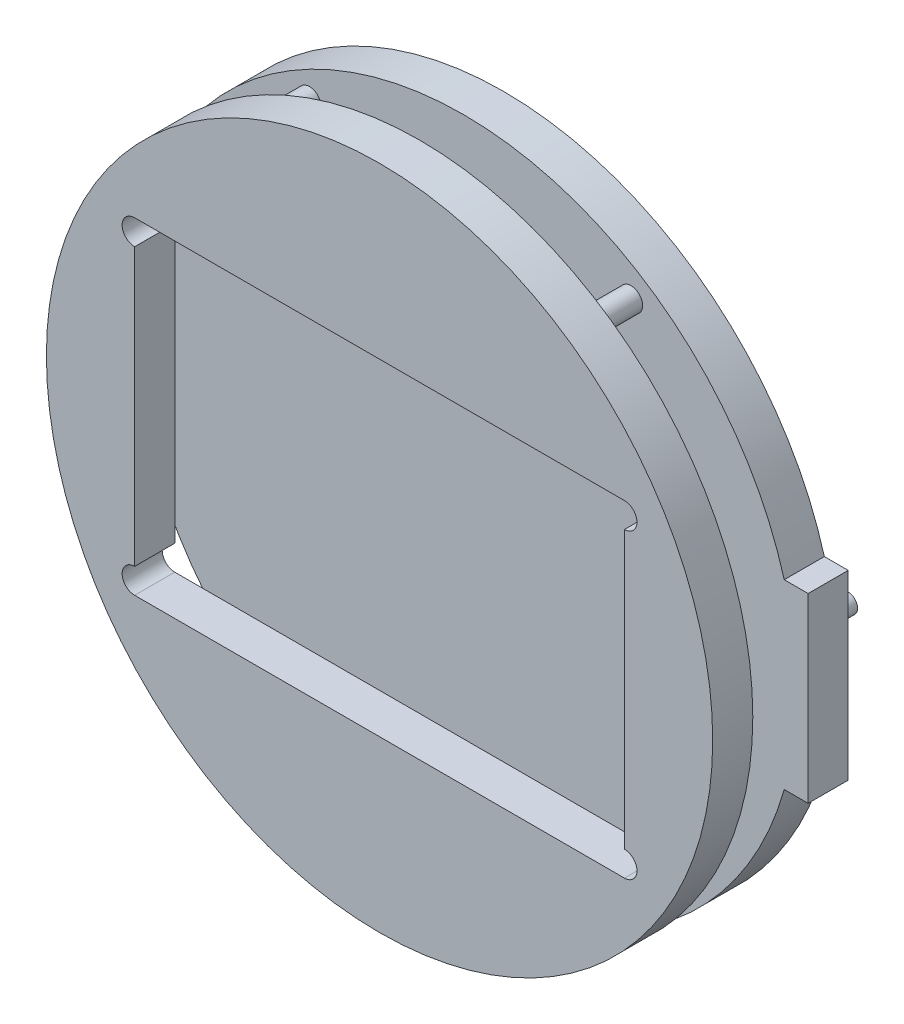
SolidWorks part; units mm, degrees
ref_plane "Front Plane" through (0, 0, 0) normal (0, 0, 1) x (1, 0, 0)
ref_plane "Top Plane" through (0, 0, 0) normal (0, 1, 0) x (1, 0, 0)
ref_plane "Right Plane" through (0, 0, 0) normal (1, 0, 0) x (0, 0, -1)
sketch "Sketch1" plane through (0, 0, 0) normal (0, 0, 1) x (1, 0, 0)
  line L1 (-10, 7.5) -> (10, 7.5)
  line L2 (-10, 7.5) -> (-10, -7.5)
  line L3 (-10, -7.5) -> (10, -7.5)
  line L4 (10, 7.5) -> (10, -7.5)
  line L5 (-10, 7.5) -> (10, -7.5) construction
  line L6 (-10, -7.5) -> (10, 7.5) construction
  circle A0 centre (0, 0) radius 12.5
  circle A1 centre (0, 0) radius 13.135
  point P10 (0, 0)
  dimension "D1" = 15
  dimension "D3" = 0.635
  dimension "D2" = 20
sketch "Sketch3" plane through (0, 0, 0) normal (0, 0, 1) x (1, 0, 0)
  line L0 (0, 0) -> (0, 12.7) construction
  line L1 (4.274, 12.409) -> (5.7523, 11.7967)
  line L2 (-0.8, 13.1) -> (0.8, 13.1)
  line L3 (-0.8, 13.1) -> (-0.8, 12.3)
  line L4 (-0.8, 12.3) -> (0.8, 12.3)
  line L5 (0.8, 13.1) -> (0.8, 12.3)
  line L6 (-0.8, 13.1) -> (0.8, 12.3) construction
  line L7 (-0.8, 12.3) -> (0.8, 13.1) construction
  line L8 (4.274, 12.409) -> (3.9679, 11.6699)
  line L9 (3.9679, 11.6699) -> (5.4461, 11.0576)
  line L10 (5.7523, 11.7967) -> (5.4461, 11.0576)
  line L11 (4.274, 12.409) -> (5.4461, 11.0576) construction
  line L12 (3.9679, 11.6699) -> (5.7523, 11.7967) construction
  line L13 (8.6974, 9.8288) -> (9.8288, 8.6974) construction
  line L14 (8.6974, 9.8288) -> (8.1317, 9.2631) construction
  line L15 (8.1317, 9.2631) -> (9.2631, 8.1317) construction
  line L16 (9.8288, 8.6974) -> (9.2631, 8.1317) construction
  line L17 (8.6974, 9.8288) -> (9.2631, 8.1317) construction
  line L18 (8.1317, 9.2631) -> (9.8288, 8.6974) construction
  line L19 (11.7967, 5.7523) -> (12.409, 4.274)
  line L20 (11.7967, 5.7523) -> (11.0576, 5.4461)
  line L21 (11.0576, 5.4461) -> (11.6699, 3.9679)
  line L22 (12.409, 4.274) -> (11.6699, 3.9679)
  line L23 (11.7967, 5.7523) -> (11.6699, 3.9679) construction
  line L24 (11.0576, 5.4461) -> (12.409, 4.274) construction
  line L25 (13.1, 0.8) -> (13.1, -0.8)
  line L26 (13.1, 0.8) -> (12.3, 0.8)
  line L27 (12.3, 0.8) -> (12.3, -0.8)
  line L28 (13.1, -0.8) -> (12.3, -0.8)
  line L29 (13.1, 0.8) -> (12.3, -0.8) construction
  line L30 (12.3, 0.8) -> (13.1, -0.8) construction
  line L31 (12.409, -4.274) -> (11.7967, -5.7523)
  line L32 (12.409, -4.274) -> (11.6699, -3.9679)
  line L33 (11.6699, -3.9679) -> (11.0576, -5.4461)
  line L34 (11.7967, -5.7523) -> (11.0576, -5.4461)
  line L35 (12.409, -4.274) -> (11.0576, -5.4461) construction
  line L36 (11.6699, -3.9679) -> (11.7967, -5.7523) construction
  line L37 (9.8288, -8.6974) -> (8.6974, -9.8288) construction
  line L38 (9.8288, -8.6974) -> (9.2631, -8.1317) construction
  line L39 (9.2631, -8.1317) -> (8.1317, -9.2631) construction
  line L40 (8.6974, -9.8288) -> (8.1317, -9.2631) construction
  line L41 (9.8288, -8.6974) -> (8.1317, -9.2631) construction
  line L42 (9.2631, -8.1317) -> (8.6974, -9.8288) construction
  line L43 (5.7523, -11.7967) -> (4.274, -12.409)
  line L44 (5.7523, -11.7967) -> (5.4461, -11.0576)
  line L45 (5.4461, -11.0576) -> (3.9679, -11.6699)
  line L46 (4.274, -12.409) -> (3.9679, -11.6699)
  line L47 (5.7523, -11.7967) -> (3.9679, -11.6699) construction
  line L48 (5.4461, -11.0576) -> (4.274, -12.409) construction
  line L49 (0.8, -13.1) -> (-0.8, -13.1)
  line L50 (0.8, -13.1) -> (0.8, -12.3)
  line L51 (0.8, -12.3) -> (-0.8, -12.3)
  line L52 (-0.8, -13.1) -> (-0.8, -12.3)
  line L53 (0.8, -13.1) -> (-0.8, -12.3) construction
  line L54 (0.8, -12.3) -> (-0.8, -13.1) construction
  line L55 (-4.274, -12.409) -> (-5.7523, -11.7967)
  line L56 (-4.274, -12.409) -> (-3.9679, -11.6699)
  line L57 (-3.9679, -11.6699) -> (-5.4461, -11.0576)
  line L58 (-5.7523, -11.7967) -> (-5.4461, -11.0576)
  line L59 (-4.274, -12.409) -> (-5.4461, -11.0576) construction
  line L60 (-3.9679, -11.6699) -> (-5.7523, -11.7967) construction
  line L61 (-8.6974, -9.8288) -> (-9.8288, -8.6974) construction
  line L62 (-8.6974, -9.8288) -> (-8.1317, -9.2631) construction
  line L63 (-8.1317, -9.2631) -> (-9.2631, -8.1317) construction
  line L64 (-9.8288, -8.6974) -> (-9.2631, -8.1317) construction
  line L65 (-8.6974, -9.8288) -> (-9.2631, -8.1317) construction
  line L66 (-8.1317, -9.2631) -> (-9.8288, -8.6974) construction
  line L67 (-11.7967, -5.7523) -> (-12.409, -4.274)
  line L68 (-11.7967, -5.7523) -> (-11.0576, -5.4461)
  line L69 (-11.0576, -5.4461) -> (-11.6699, -3.9679)
  line L70 (-12.409, -4.274) -> (-11.6699, -3.9679)
  line L71 (-11.7967, -5.7523) -> (-11.6699, -3.9679) construction
  line L72 (-11.0576, -5.4461) -> (-12.409, -4.274) construction
  line L73 (-13.1, -0.8) -> (-13.1, 0.8)
  line L74 (-13.1, -0.8) -> (-12.3, -0.8)
  line L75 (-12.3, -0.8) -> (-12.3, 0.8)
  line L76 (-13.1, 0.8) -> (-12.3, 0.8)
  line L77 (-13.1, -0.8) -> (-12.3, 0.8) construction
  line L78 (-12.3, -0.8) -> (-13.1, 0.8) construction
  line L79 (-12.409, 4.274) -> (-11.7967, 5.7523)
  line L80 (-12.409, 4.274) -> (-11.6699, 3.9679)
  line L81 (-11.6699, 3.9679) -> (-11.0576, 5.4461)
  line L82 (-11.7967, 5.7523) -> (-11.0576, 5.4461)
  line L83 (-12.409, 4.274) -> (-11.0576, 5.4461) construction
  line L84 (-11.6699, 3.9679) -> (-11.7967, 5.7523) construction
  line L85 (-9.8288, 8.6974) -> (-8.6974, 9.8288) construction
  line L86 (-9.8288, 8.6974) -> (-9.2631, 8.1317) construction
  line L87 (-9.2631, 8.1317) -> (-8.1317, 9.2631) construction
  line L88 (-8.6974, 9.8288) -> (-8.1317, 9.2631) construction
  line L89 (-9.8288, 8.6974) -> (-8.1317, 9.2631) construction
  line L90 (-9.2631, 8.1317) -> (-8.6974, 9.8288) construction
  line L91 (-5.7523, 11.7967) -> (-4.274, 12.409)
  line L92 (-5.7523, 11.7967) -> (-5.4461, 11.0576)
  line L93 (-5.4461, 11.0576) -> (-3.9679, 11.6699)
  line L94 (-4.274, 12.409) -> (-3.9679, 11.6699)
  line L95 (-5.7523, 11.7967) -> (-3.9679, 11.6699) construction
  line L96 (-5.4461, 11.0576) -> (-4.274, 12.409) construction
  point P77 (0, 0)
  dimension "D1" = 1.6
  dimension "D2" = 0.8
  dimension "D3" = 12.7
  dimension "D4" = 16
sketch "Sketch4" plane through (0, 0, 0) normal (0, 0, 1) x (1, 0, 0)
  circle A0 centre (0, 0) radius 13.1244
  circle A1 centre (0, 0) radius 13.5054
  dimension "D1" = 0.381
sketch "Sketch5" plane through (0, 0, 0) normal (0, 0, 1) x (1, 0, 0)
  circle A0 centre (0, 0) radius 13.5054 construction
  circle A1 centre (0, 0) radius 13.5054
extrude "Boss-Extrude1" add sketch "Sketch5" along normal blind 1.6256
sketch "Sketch6" plane through (0, 0, 1.6256) normal (0, 0, 1) x (1, 0, 0)
  line L0 (-9.927, 6.627) -> (9.927, 6.627)
  line L1 (-9.8, 6.5) -> (9.8, 6.5) construction
  line L2 (-9.8, 6.5) -> (-9.8, -6.5) construction
  line L3 (-9.8, -6.5) -> (9.8, -6.5) construction
  line L4 (9.8, 6.5) -> (9.8, -6.5) construction
  line L5 (-9.8, 6.5) -> (9.8, -6.5) construction
  line L6 (-9.8, -6.5) -> (9.8, 6.5) construction
  line L7 (9.927, 6.627) -> (9.927, -6.627)
  line L8 (-9.927, -6.627) -> (9.927, -6.627)
  line L9 (-9.927, 6.627) -> (-9.927, -6.627)
  point P0 (0, 0)
  dimension "D1" = 13
  dimension "D2" = 19.6
  dimension "D3" = 0.127
extrude "Cut-Extrude1" cut sketch "Sketch6" against normal through all
sketch "Sketch7" plane through (0, 0, 1.6256) normal (0, 0, 1) x (1, 0, 0)
  line L0 (-9.927, 6.627) -> (-9.927, -6.627) construction
  line L1 (9.927, -6.627) -> (9.927, 6.627) construction
  line L2 (9.927, 6.627) -> (-9.927, 6.627) construction
  circle A0 centre (-9.927, 6.119) radius 0.508
  circle A1 centre (-9.927, -6.119) radius 0.508
  circle A2 centre (9.927, -6.119) radius 0.508
  circle A3 centre (9.927, 6.119) radius 0.508
  dimension "D1" = 1.016
extrude "Cut-Extrude2" cut sketch "Sketch7" against normal through all
sketch "Sketch8" plane through (0, 0, 0) normal (0, 0, -1) x (-1, 0, 0)
  line L0 (3.5728, 9.9688) -> (4.8428, 9.9688)
  line L2 (4.8428, 8.6988) -> (6.1128, 8.6988)
  line L3 (4.8428, 8.6988) -> (4.8428, 9.9688)
  line L4 (4.8428, 9.9688) -> (6.1128, 9.9688)
  line L5 (6.1128, 8.6988) -> (6.1128, 9.9688)
  line L6 (3.5728, 8.6988) -> (3.5728, 9.9688)
  line L7 (3.5728, 8.6988) -> (4.8428, 8.6988)
  line L8 (4.8428, 8.6988) -> (4.8428, 9.9688)
  line L9 (2.3028, 9.9688) -> (3.5728, 9.9688)
  line L10 (2.3028, 8.6988) -> (2.3028, 9.9688)
  line L11 (2.3028, 8.6988) -> (3.5728, 8.6988)
  line L12 (3.5728, 8.6988) -> (3.5728, 9.9688)
  line L13 (1.0328, 9.9688) -> (2.3028, 9.9688)
  line L14 (1.0328, 8.6988) -> (1.0328, 9.9688)
  line L15 (1.0328, 8.6988) -> (2.3028, 8.6988)
  line L16 (2.3028, 8.6988) -> (2.3028, 9.9688)
  line L17 (-0.2372, 9.9688) -> (1.0328, 9.9688)
  line L18 (-0.2372, 8.6988) -> (-0.2372, 9.9688)
  line L19 (-0.2372, 8.6988) -> (1.0328, 8.6988)
  line L20 (1.0328, 8.6988) -> (1.0328, 9.9688)
  line L21 (-1.5072, 9.9688) -> (-0.2372, 9.9688)
  line L22 (-1.5072, 8.6988) -> (-1.5072, 9.9688)
  line L23 (-1.5072, 8.6988) -> (-0.2372, 8.6988)
  line L24 (-0.2372, 8.6988) -> (-0.2372, 9.9688)
  line L25 (-2.7772, 9.9688) -> (-1.5072, 9.9688)
  line L26 (-2.7772, 8.6988) -> (-2.7772, 9.9688)
  line L27 (-2.7772, 8.6988) -> (-1.5072, 8.6988)
  line L28 (-1.5072, 8.6988) -> (-1.5072, 9.9688)
  line L29 (-4.0472, 9.9688) -> (-2.7772, 9.9688)
  line L30 (-4.0472, 8.6988) -> (-4.0472, 9.9688)
  line L31 (-4.0472, 8.6988) -> (-2.7772, 8.6988)
  line L32 (-2.7772, 8.6988) -> (-2.7772, 9.9688)
  line L33 (-5.3172, 9.9688) -> (-4.0472, 9.9688)
  line L34 (-5.3172, 8.6988) -> (-5.3172, 9.9688)
  line L35 (-5.3172, 8.6988) -> (-4.0472, 8.6988)
  line L36 (-4.0472, 8.6988) -> (-4.0472, 9.9688)
  line L37 (-6.5872, 9.9688) -> (-5.3172, 9.9688)
  line L38 (-6.5872, 8.6988) -> (-6.5872, 9.9688)
  line L39 (-6.5872, 8.6988) -> (-5.3172, 8.6988)
  line L40 (-5.3172, 8.6988) -> (-5.3172, 9.9688)
  line L42 (3.5728, 9.9688) -> (3.5728, 11.2388)
  line L43 (3.5728, 9.9688) -> (4.8428, 9.9688)
  line L45 (2.3028, 11.2388) -> (3.5728, 11.2388)
  line L46 (2.3028, 9.9688) -> (2.3028, 11.2388)
  line L47 (2.3028, 9.9688) -> (3.5728, 9.9688)
  line L48 (3.5728, 9.9688) -> (3.5728, 11.2388)
  line L49 (1.0328, 11.2388) -> (2.3028, 11.2388)
  line L50 (1.0328, 9.9688) -> (1.0328, 11.2388)
  line L51 (1.0328, 9.9688) -> (2.3028, 9.9688)
  line L52 (2.3028, 9.9688) -> (2.3028, 11.2388)
  line L53 (-0.2372, 11.2388) -> (1.0328, 11.2388)
  line L54 (-0.2372, 9.9688) -> (-0.2372, 11.2388)
  line L55 (-0.2372, 9.9688) -> (1.0328, 9.9688)
  line L56 (1.0328, 9.9688) -> (1.0328, 11.2388)
  line L57 (-1.5072, 11.2388) -> (-0.2372, 11.2388)
  line L58 (-1.5072, 9.9688) -> (-1.5072, 11.2388)
  line L59 (-1.5072, 9.9688) -> (-0.2372, 9.9688)
  line L60 (-0.2372, 9.9688) -> (-0.2372, 11.2388)
  line L61 (-2.7772, 11.2388) -> (-1.5072, 11.2388)
  line L62 (-2.7772, 9.9688) -> (-2.7772, 11.2388)
  line L63 (-2.7772, 9.9688) -> (-1.5072, 9.9688)
  line L64 (-1.5072, 9.9688) -> (-1.5072, 11.2388)
  line L65 (-4.0472, 11.2388) -> (-2.7772, 11.2388)
  line L66 (-4.0472, 9.9688) -> (-4.0472, 11.2388)
  line L67 (-4.0472, 9.9688) -> (-2.7772, 9.9688)
  line L68 (-2.7772, 9.9688) -> (-2.7772, 11.2388)
  line L71 (-5.3172, 9.9688) -> (-4.0472, 9.9688)
  line L72 (-4.0472, 9.9688) -> (-4.0472, 11.2388)
  line L75 (-6.5872, 9.9688) -> (-5.3172, 9.9688)
  line L79 (4.8428, 9.9688) -> (6.1128, 9.9688)
  line L81 (-5.3172, 11.2388) -> (-4.0472, 11.2388)
  line L82 (-5.3172, 9.9688) -> (-5.3172, 11.2388)
  line L83 (-6.5872, 11.2388) -> (-5.3172, 11.2388)
  line L84 (-6.5872, 9.9688) -> (-6.5872, 11.2388)
  line L85 (-5.3172, 9.9688) -> (-5.3172, 11.2388)
  line L86 (3.5728, 11.2388) -> (4.8428, 11.2388)
  line L87 (4.8428, 9.9688) -> (4.8428, 11.2388)
  line L88 (4.8428, 11.2388) -> (6.1128, 11.2388)
  line L89 (4.8428, 9.9688) -> (4.8428, 11.2388)
  line L90 (6.1128, 9.9688) -> (6.1128, 11.2388)
  dimension "D1" = 10
  dimension "D2" = 2
sketch "Sketch9" plane through (0, 0, 0) normal (0, 0, -1) x (-1, 0, 0)
  line L0 (0, 13.5054) -> (0, -13.5054) construction
  circle A0 centre (0, 0) radius 13.5054 construction
  circle A1 centre (-6.7915, 10.4337) radius 0.468
  circle A2 centre (6.2438, 10.9017) radius 0.4712
  circle A3 centre (5.4223, -10.7624) radius 0.6124
  circle A4 centre (-6.7915, -10.15) radius 0.6124
extrude "Boss-Extrude2" add sketch "Sketch9" along normal blind 1.778
sketch "Sketch10" plane through (0, 0, -1.778) normal (0, 0, -1) x (-1, 0, 0)
  circle A0 centre (0, 0) radius 13.5128
  dimension "D1" = 27.0256
extrude "Boss-Extrude3" add sketch "Sketch10" along normal blind 1.6256
sketch "Sketch11" plane through (0, 0, -3.4036) normal (0, 0, -1) x (-1, 0, 0)
  line L1 (-13.97, 3.683) -> (13.97, 3.683)
  line L2 (-13.97, 3.683) -> (-13.97, -3.683)
  line L3 (-13.97, -3.683) -> (13.97, -3.683)
  line L4 (13.97, 3.683) -> (13.97, -3.683)
  line L5 (-13.97, 3.683) -> (13.97, -3.683) construction
  line L6 (-13.97, -3.683) -> (13.97, 3.683) construction
  point P0 (0, 0)
extrude "Boss-Extrude4" add sketch "Sketch11" against normal up to surface (1.6256 mm away) up to face at (-6.715, 10.9017, -1.778)
sketch "Sketch12" plane through (0, 0, -3.4036) normal (0, 0, -1) x (-1, 0, 0)
  line L0 (0, 13.5128) -> (0, -13.5128) construction
  line L1 (0, 0) -> (-11.43, 0) construction
  arc A0 (13.0012, 3.683) -> (-13.0012, 3.683) centre (0, 0) ccw construction
  arc A1 (-13.0012, -3.683) -> (13.0012, -3.683) centre (0, 0) ccw construction
  circle A2 centre (-11.43, 0) radius 0.381
  circle A3 centre (11.43, 0) radius 0.381
  dimension "D1" = 11.43
extrude "Boss-Extrude5" add sketch "Sketch12" along normal blind 2.54
